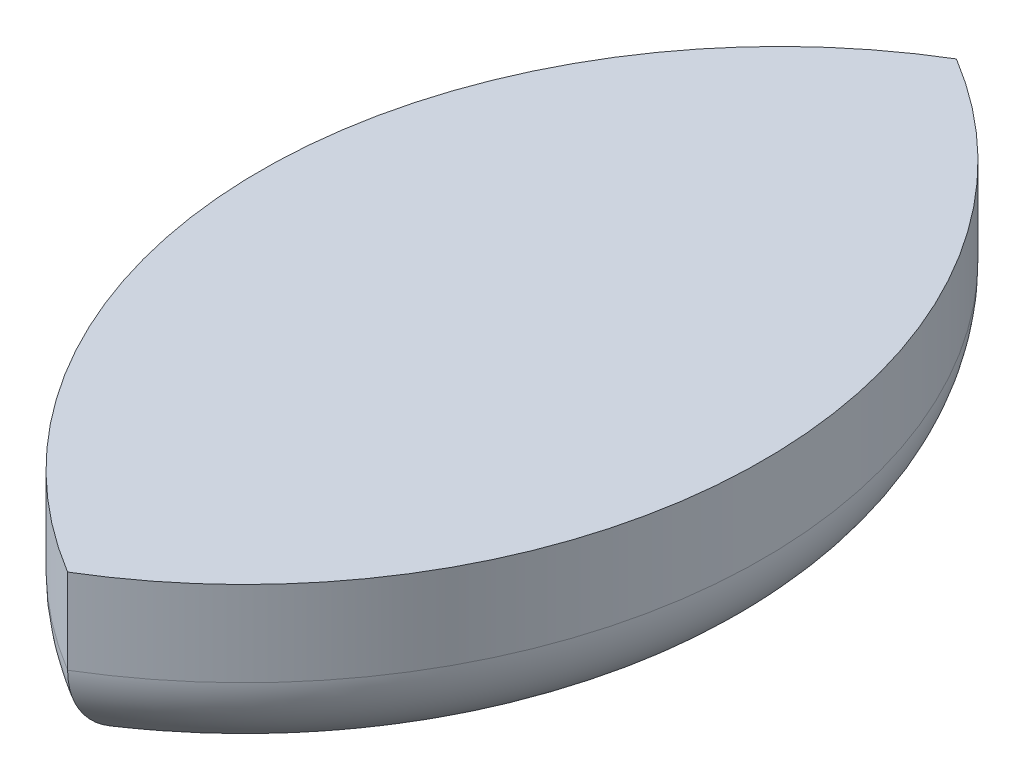
SolidWorks part; units mm, degrees
ref_plane "Front Plane" through (0, 0, 0) normal (0, 0, 1) x (1, 0, 0)
ref_plane "Top Plane" through (0, 0, 0) normal (0, 1, 0) x (1, 0, 0)
ref_plane "Right Plane" through (0, 0, 0) normal (1, 0, 0) x (0, 0, -1)
sketch "Sketch1" plane through (0, 0, 0) normal (0, 1, 0) x (1, 0, 0)
  line L1 (-108.4125, -132.7) -> (108.4125, -132.7)
  line L2 (-108.4125, -132.7) -> (-108.4125, 132.7)
  line L3 (-108.4125, 132.7) -> (108.4125, 132.7)
  line L4 (108.4125, -132.7) -> (108.4125, 132.7)
  line L5 (-108.4125, -132.7) -> (108.4125, 132.7) construction
  line L6 (-108.4125, 132.7) -> (108.4125, -132.7) construction
  arc A0 (0, 132.7) -> (0, -132.7) centre (-79.8953, 0) cw
  arc A1 (0, 132.7) -> (0, -132.7) centre (79.8953, 0) ccw
  point P0 (0, 0)
  point P10 (-75, 0)
  point P11 (75, 0)
  dimension "D1" = 216.825
  dimension "D2" = 265.4
  dimension "D3" = 150
extrude "Boss-Extrude1" add sketch "Sketch1" along normal blind 50.8 contours A0 A1
fillet "Fillet1" radius 25.4 2 edges at (75, 0, 0) (-75, 0, 0)
